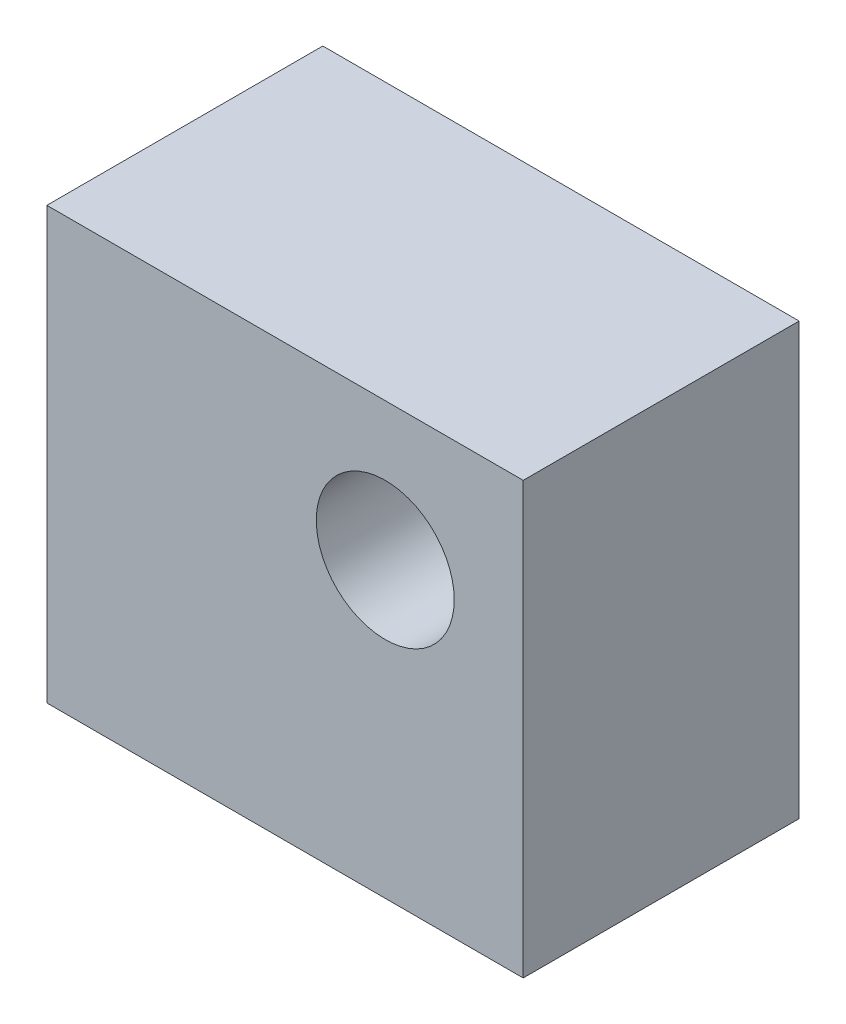
SolidWorks part; units mm, degrees
material "1060 Alloy"
ref_plane "Front" through (0, 0, 0) normal (0, 0, 1) x (1, 0, 0)
ref_plane "Top" through (0, 0, 0) normal (0, 1, 0) x (1, 0, 0)
ref_plane "Right" through (0, 0, 0) normal (1, 0, 0) x (0, 0, -1)
sketch "Sketch3" plane through (0, 0, 0) normal (0, 0, 1) x (1, 0, 0)
  line L0 (-0.127, -6.35) -> (30.1755, -6.35)
  line L1 (0, 0) -> (21.9242, 0)
  line L2 (0, 0) -> (0, -19.8376)
  line L3 (0, -19.8376) -> (21.9242, -19.8376)
  line L4 (21.9242, 0) -> (21.9242, -19.8376)
  line L5 (15.5742, -19.8376) -> (15.5742, 0) construction
  line L6 (15.5742, -6.35) -> (8.0621, -19.3614) construction
  line L15 (12.5496, -11.5887) -> (15.5742, -13.335) construction
  circle A0 centre (15.5742, -6.35) radius 6.0492 construction
  point P14 (0, -6.35)
  point P17 (9.525, -6.35)
  point P20 (7.7871, -19.8376)
  dimension "D2" = 6.35
  dimension "D6" = 3.4925
  dimension "D3" = 60
  dimension "D1" = 9.525
  dimension "D4" = 9.525
  dimension "D5" = 6.35
extrude "Boss-Extrude1" add sketch "Sketch3" along normal mid plane 12.7
sketch "Sketch4" plane through (0, 0, 0) normal (-1, 0, 0) x (0, 0, 1)
  circle A0 centre (0, -6.35) radius 3.175
  dimension "D1" = 6.35
extrude "Cut-Extrude1" cut sketch "Sketch4" against normal blind 9.525
ref_plane "Plane1" through (7.7871, -19.8376, 0) normal (-0.5, -0.866, 0) x (-0.866, 0.5, 0)
ref_plane "Mirror Plane" through (15.5742, 0, 0) normal (-1, 0, 0) x (0, 0, 1)
sketch "Sketch5" plane through (7.7871, -19.8376, 0) normal (-0.5, -0.866, 0) x (-0.866, 0.5, 0)
  circle A0 centre (0, 0) radius 3.175
  dimension "D1" = 6.35
extrude "Cut-Extrude5" cut sketch "Sketch5" against normal blind 9.525 and the other way up to next
sketch "Sketch6" plane through (0, 0, 6.35) normal (0, 0, -1) x (-1, 0, 0)
  circle A0 centre (-15.5742, -6.35) radius 3.175
  dimension "D1" = 6.35
extrude "Cut-Extrude6" cut sketch "Sketch6" along normal blind 9.525
equation "\"truss_member_od\" = .25in"
equation "\"truss_member_id\"= 0in"
equation "\"truss_member_L1\" = 2.125in"
equation "\"connector_hole_depth\" = .375in"
equation "\"D1@Boss-Extrude1\"=\"truss_member_od\"*2"
equation "\"D6@Sketch3\"=\"truss_member_od\"/2*1.1"
equation "\"D1@Sketch4\"=\"truss_member_od\""
equation "\"D1@Cut-Extrude1\"=\"connector_hole_depth\""
equation "\"D1@Sketch3\"=\"connector_hole_depth\""
equation "\"D4@Sketch3\"=\"connector_hole_depth\""
equation "\"D1@Sketch5\"=\"truss_member_od\""
equation "\"D1@Cut-Extrude5\"=\"connector_hole_depth\""
equation "\"D1@Cut-Extrude6\"=\"connector_hole_depth\""
equation "\"D1@Sketch6\"=\"truss_member_od\""
equation "\"D5@Sketch3\"=\"truss_member_od\""
